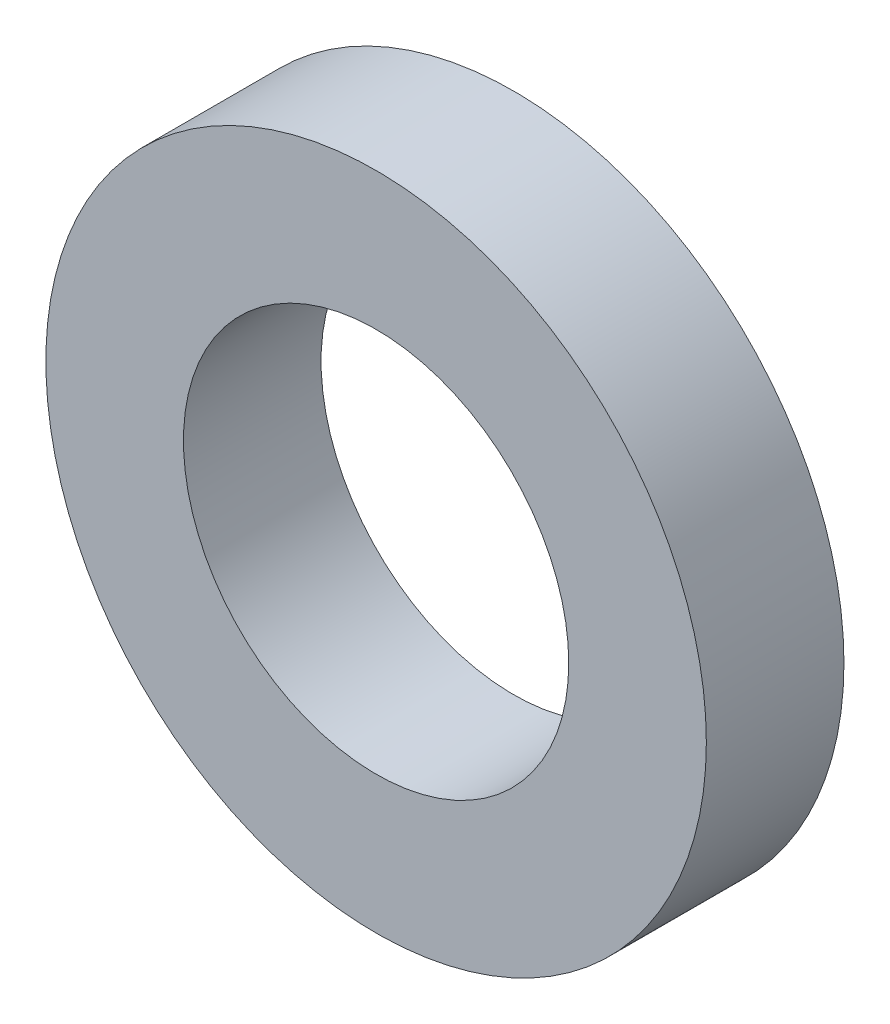
SolidWorks part; units mm, degrees
ref_plane "Front Plane" through (0, 0, 0) normal (0, 0, 1) x (1, 0, 0)
ref_plane "Top Plane" through (0, 0, 0) normal (0, 1, 0) x (1, 0, 0)
ref_plane "Right Plane" through (0, 0, 0) normal (1, 0, 0) x (0, 0, -1)
sketch "Sketch1" plane through (0, 0, 0) normal (0, 0, 1) x (1, 0, 0)
  circle A0 centre (0, 0) radius 2.4
  circle A1 centre (0, 0) radius 1.4
  dimension "D1" = 4.8
  dimension "D2" = 2.8
extrude "Boss-Extrude1" add sketch "Sketch1" along normal blind 1
